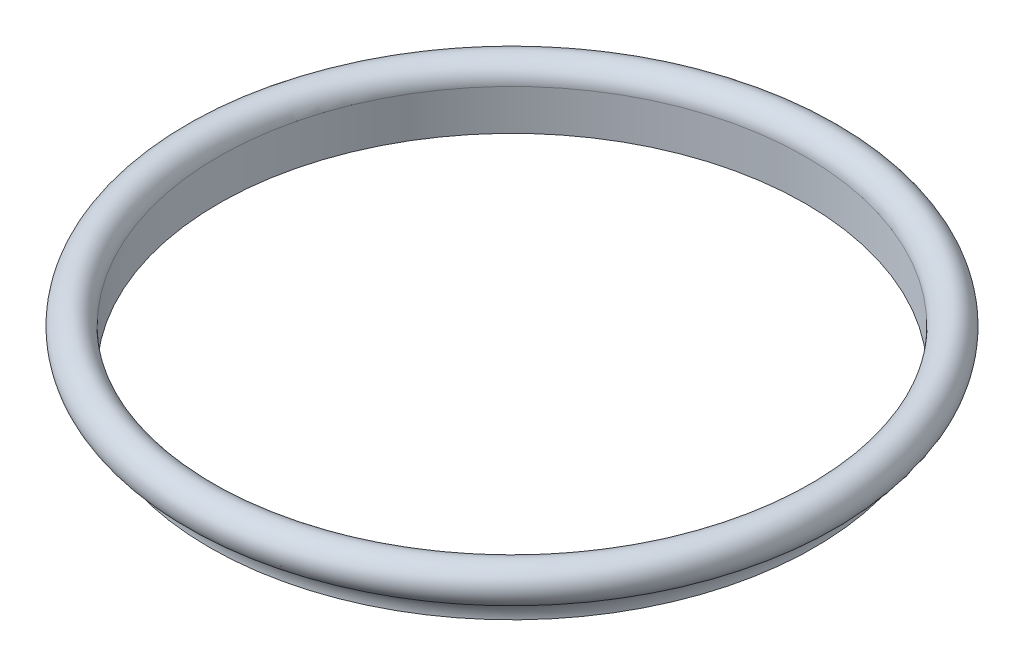
SolidWorks part; units mm, degrees
ref_plane "Front Plane" through (0, 0, 0) normal (0, 0, 1) x (1, 0, 0)
ref_plane "Top Plane" through (0, 0, 0) normal (0, 1, 0) x (1, 0, 0)
ref_plane "Right Plane" through (0, 0, 0) normal (1, 0, 0) x (0, 0, -1)
sketch "Sketch1" plane through (0, 0, 0) normal (0, 0, 1) x (1, 0, 0)
  line L7 (82.55, 0) -> (82.55, 11.43)
  line L8 (85.09, 0) -> (82.55, 0)
  line L9 (0, 0) -> (0, 14.8903) construction
  arc A5 (82.55, 11.43) -> (90.7235, 7.4005) centre (87.63, 11.43) cw
  arc A6 (90.7235, 7.4005) -> (85.09, 0) centre (92.0538, 0.5434) ccw
  dimension "D1" = 2.54
  dimension "D3" = 5.08
  dimension "D4" = 6.985
  dimension "D2" = 11.43
  dimension "D5" = 82.55
revolve "Revolve1" add sketch "Sketch1" angle 360 about L9
